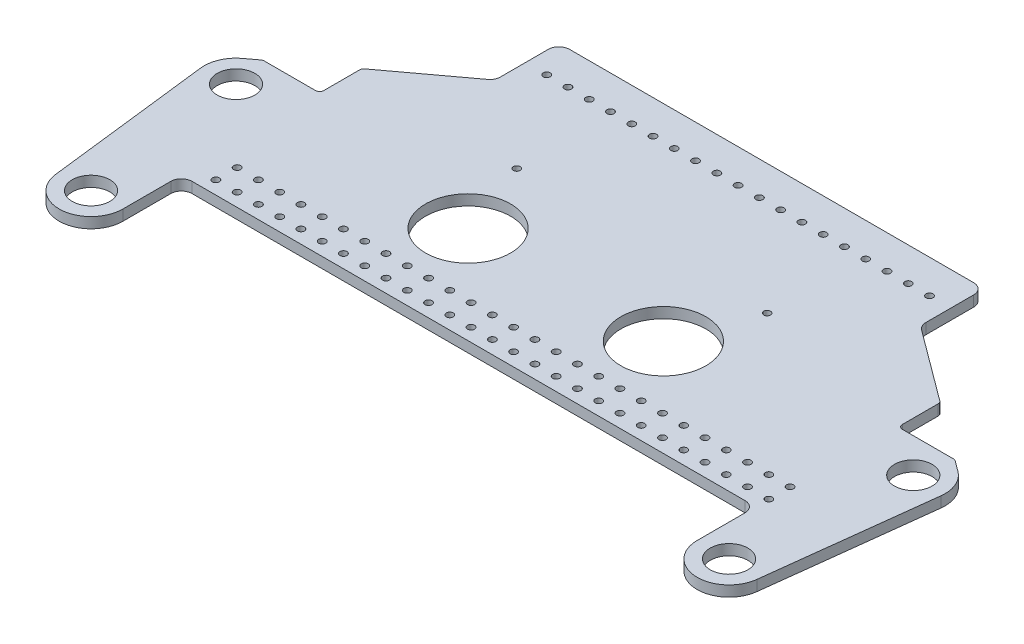
SolidWorks part; units mm, degrees
material "Air"
ref_plane "Front" through (0, 0, 0) normal (0, 0, 1) x (1, 0, 0)
ref_plane "Top" through (0, 0, 0) normal (0, 1, 0) x (1, 0, 0)
ref_plane "Right" through (0, 0, 0) normal (1, 0, 0) x (0, 0, -1)
sketch "Sketch1" plane through (0, 0, 0) normal (0, 1, 0) x (1, 0, 0)
  line L0 (0, 0) -> (0, 105.6961) construction
  line L1 (-202.2177, 98.3041) -> (-190.5, 0) construction
  line L2 (-127, 215.9) -> (127, 215.9)
  line L3 (-127, 215.9) -> (-127, 177.8)
  line L4 (-127, 177.8) -> (127, 177.8) construction
  line L5 (127, 215.9) -> (127, 177.8)
  line L6 (-190.839, 99.6604) -> (-179.1214, 1.3563) construction
  line L7 (-213.5963, 96.9478) -> (-201.8786, -1.3563) construction
  line L8 (-202.2177, 98.3041) -> (-58.3167, 92.964) construction
  line L9 (-201.7927, 109.7554) -> (-57.8917, 104.4153) construction
  line L10 (-202.6426, 86.8528) -> (-58.7416, 81.5127) construction
  line L11 (-190.5, 0) -> (-190.5, 152.4) construction
  line L12 (-190.5, 152.4) -> (74.7667, 138.4884) construction
  line L13 (-190.5, 0) -> (-127.3007, 138.6781) construction
  line L14 (-127.3007, 138.6781) -> (74.7667, 138.4884) construction
  line L15 (-209.55, 165.4952) -> (-209.55, -81.8808) construction
  line L16 (-171.45, 0) -> (-171.45, 34.925)
  line L17 (-205.8838, 91.9541) -> (-198.5515, 91.9541) construction
  line L18 (-198.5515, 91.9541) -> (-194.8853, 98.3041) construction
  line L19 (-194.8853, 98.3041) -> (-198.5515, 104.6541) construction
  line L20 (-198.5515, 104.6541) -> (-205.8838, 104.6541) construction
  line L21 (-205.8838, 104.6541) -> (-209.55, 98.3041) construction
  line L22 (-209.55, 98.3041) -> (-205.8838, 91.9541) construction
  line L23 (-171.45, 34.925) -> (171.45, 34.925)
  line L24 (171.45, 0) -> (171.45, 34.925)
  line L26 (-221.1337, 96.0493) -> (-209.4161, -2.2548)
  line L27 (-79.3225, 115.189) -> (-37.3109, 115.189) construction
  line L28 (-79.3225, 115.189) -> (-79.3225, 70.739) construction
  line L29 (-79.3225, 70.739) -> (-37.3109, 70.739) construction
  line L30 (-37.3109, 115.189) -> (-37.3109, 70.739) construction
  line L31 (-79.3225, 115.189) -> (-37.3109, 70.739) construction
  line L32 (-79.3225, 70.739) -> (-37.3109, 115.189) construction
  line L33 (-213.565, 113.6058) -> (-127, 177.8)
  line L34 (213.565, 113.6058) -> (127, 177.8)
  line L35 (221.1337, 96.0493) -> (209.4161, -2.2548)
  line L36 (-171.45, 34.925) -> (-171.45, 73.025) construction
  line L37 (-171.45, 73.025) -> (171.45, 73.025) construction
  line L38 (171.45, 73.025) -> (171.45, 34.925) construction
  line L39 (-177.8, 131.8554) -> (-177.8, -43.5528) construction
  line L40 (-440.324, 48.2727) -> (417.5697, 48.2727) construction
  circle A0 centre (-74.7667, 138.4884) radius 2.0193
  circle A1 centre (-190.5, 0) radius 11.2395
  circle A2 centre (74.7667, 138.4884) radius 2.0193
  circle A3 centre (190.5, 0) radius 11.2395
  circle A4 centre (-190.5, 0) radius 19.05 construction
  circle A5 centre (190.5, 0) radius 19.05 construction
  circle A6 centre (-202.2177, 98.3041) radius 11.2395
  arc A8 (-190.839, 99.6604) -> (-213.5963, 96.9478) centre (-202.2177, 98.3041) ccw construction
  arc A9 (-201.8786, -1.3563) -> (-179.1214, 1.3563) centre (-190.5, 0) ccw construction
  arc A10 (-201.7927, 109.7554) -> (-202.6426, 86.8528) centre (-202.2177, 98.3041) ccw construction
  arc A11 (-58.7416, 81.5127) -> (-57.8917, 104.4153) centre (-58.3167, 92.964) ccw construction
  circle A12 centre (-202.2177, 98.3041) radius 6.35 construction
  circle A13 centre (-202.2177, 98.3041) radius 7.3323 construction
  circle A14 centre (-202.2177, 98.3041) radius 19.05 construction
  arc A18 (-209.4161, -2.2548) -> (-171.45, 0) centre (-190.5, 0) ccw
  arc A19 (-221.1337, 96.0493) -> (-213.565, 113.6058) centre (-202.2177, 98.3041) cw
  arc A22 (221.1337, 96.0493) -> (213.565, 113.6058) centre (202.2177, 98.3041) ccw
  circle A23 centre (202.2177, 98.3041) radius 11.2395
  arc A24 (209.4161, -2.2548) -> (171.45, 0) centre (190.5, 0) cw
  circle A25 centre (-58.3167, 92.964) radius 25.4
  circle A26 centre (58.3167, 92.964) radius 25.4
  point P19 (-196.3588, 49.1521)
  point P24 (-130.2672, 95.6341)
  dimension "D4" = 22.479
  dimension "D5" = 38.1
  dimension "D6" = 4.0386
  dimension "D25" = 22.479
  dimension "D26" = 50.8
  dimension "D2" = 138.4884
  dimension "D7" = 254
  dimension "D8" = 38.1
  dimension "D9" = 22.9183
  dimension "D10" = 152.4
  dimension "D11" = 24.5
  dimension "D12" = 19.05
  dimension "D16" = 12.7
  dimension "D14" = 34.925
  dimension "D17" = 25.4
  dimension "D21" = 44.45
  dimension "D22" = 42.0116
  dimension "D24" = 38.1
  dimension "D23" = 2.286
  dimension "D27" = 177.8
  dimension "D28" = 167.6273
  dimension "D3" = 265.2667
  dimension "D29" = 342.9
extrude "Boss-Extrude1" add sketch "Sketch1" along normal mid plane 6.35
fillet "Fillet1" radius 6.35 6 edges at (-127, 0, -177.8) (-127, 0, -215.9) (127, 0, -215.9) (127, 0, -177.8) (171.45, 0, -34.925) (-171.45, 0, -34.925)
sketch "Sketch2" plane through (0, 3.175, 0) normal (0, 1, 0) x (1, 0, 0)
  line L0 (-127, 195.9049) -> (127, 195.9049) construction
  line L2 (127, 209.55) -> (127, 180.9965) construction
  line L3 (0, 195.9049) -> (0, 215.9) construction
  line L4 (-120.65, 215.9) -> (120.65, 215.9) construction
  circle A0 centre (0, 208.6049) radius 2.0828 construction
  circle A1 centre (12.7, 208.6049) radius 2.0828 construction
  circle A2 centre (25.4, 208.6049) radius 2.0828 construction
  circle A3 centre (38.1, 208.6049) radius 2.0828 construction
  circle A4 centre (50.8, 208.6049) radius 2.0828 construction
  circle A5 centre (63.5, 208.6049) radius 2.0828 construction
  circle A6 centre (76.2, 208.6049) radius 2.0828 construction
  circle A7 centre (88.9, 208.6049) radius 2.0828 construction
  circle A8 centre (101.6, 208.6049) radius 2.0828 construction
  circle A9 centre (114.3, 208.6049) radius 2.0828 construction
  circle A10 centre (12.7, 195.9049) radius 2.0828
  circle A11 centre (25.4, 195.9049) radius 2.0828
  circle A12 centre (38.1, 195.9049) radius 2.0828
  circle A13 centre (50.8, 195.9049) radius 2.0828
  circle A14 centre (63.5, 195.9049) radius 2.0828
  circle A15 centre (76.2, 195.9049) radius 2.0828
  circle A16 centre (88.9, 195.9049) radius 2.0828
  circle A17 centre (101.6, 195.9049) radius 2.0828
  circle A18 centre (114.3, 195.9049) radius 2.0828
  circle A19 centre (12.7, 183.2049) radius 2.0828 construction
  circle A20 centre (25.4, 183.2049) radius 2.0828 construction
  circle A21 centre (38.1, 183.2049) radius 2.0828 construction
  circle A22 centre (50.8, 183.2049) radius 2.0828 construction
  circle A23 centre (63.5, 183.2049) radius 2.0828 construction
  circle A24 centre (76.2, 183.2049) radius 2.0828 construction
  circle A25 centre (88.9, 183.2049) radius 2.0828 construction
  circle A26 centre (101.6, 183.2049) radius 2.0828 construction
  circle A27 centre (114.3, 183.2049) radius 2.0828 construction
  circle A29 centre (0, 183.2049) radius 2.0828 construction
  circle A33 centre (0, 183.2049) radius 2.0828 construction
  circle A34 centre (0, 195.9049) radius 2.0828
  circle A35 centre (-114.3, 183.2049) radius 2.0828 construction
  circle A36 centre (-101.6, 183.2049) radius 2.0828 construction
  circle A37 centre (-88.9, 183.2049) radius 2.0828 construction
  circle A38 centre (-76.2, 183.2049) radius 2.0828 construction
  circle A39 centre (-63.5, 183.2049) radius 2.0828 construction
  circle A40 centre (-50.8, 183.2049) radius 2.0828 construction
  circle A41 centre (-38.1, 183.2049) radius 2.0828 construction
  circle A42 centre (-25.4, 183.2049) radius 2.0828 construction
  circle A43 centre (-12.7, 183.2049) radius 2.0828 construction
  circle A44 centre (-114.3, 195.9049) radius 2.0828
  circle A45 centre (-101.6, 195.9049) radius 2.0828
  circle A46 centre (-88.9, 195.9049) radius 2.0828
  circle A47 centre (-76.2, 195.9049) radius 2.0828
  circle A48 centre (-63.5, 195.9049) radius 2.0828
  circle A49 centre (-50.8, 195.9049) radius 2.0828
  circle A50 centre (-38.1, 195.9049) radius 2.0828
  circle A51 centre (-25.4, 195.9049) radius 2.0828
  circle A52 centre (-12.7, 195.9049) radius 2.0828
  circle A53 centre (-114.3, 208.6049) radius 2.0828 construction
  circle A54 centre (-101.6, 208.6049) radius 2.0828 construction
  circle A55 centre (-88.9, 208.6049) radius 2.0828 construction
  circle A56 centre (-76.2, 208.6049) radius 2.0828 construction
  circle A57 centre (-63.5, 208.6049) radius 2.0828 construction
  circle A58 centre (-50.8, 208.6049) radius 2.0828 construction
  circle A59 centre (-38.1, 208.6049) radius 2.0828 construction
  circle A60 centre (-25.4, 208.6049) radius 2.0828 construction
  circle A61 centre (-12.7, 208.6049) radius 2.0828 construction
  circle A62 centre (0, 208.6049) radius 2.0828 construction
  circle A63 centre (0, 195.9049) radius 2.0828 [skipped]
  dimension "D1" = 4.1656
  dimension "D4" = 12.7
  dimension "D5" = 19.9951
  dimension "D6" = 12.7
  dimension "D7" = 12.7
  dimension "D2" = 10
  dimension "D3" = 3
extrude "Cut-Extrude1" cut sketch "Sketch2" against normal through all
sketch "Sketch3" plane through (0, 3.175, 0) normal (0, 1, 0) x (1, 0, 0)
  line L0 (-165.1, 34.925) -> (165.1, 34.925) construction
  line L1 (0, -18.3754) -> (0, 153.3377) construction
  circle A0 centre (0, 42.799) radius 2.0828 construction
  circle A1 centre (12.7, 42.799) radius 2.0828 construction
  circle A2 centre (25.4, 42.799) radius 2.0828 construction
  circle A3 centre (38.1, 42.799) radius 2.0828 construction
  circle A4 centre (50.8, 42.799) radius 2.0828 construction
  circle A5 centre (63.5, 42.799) radius 2.0828 construction
  circle A6 centre (76.2, 42.799) radius 2.0828 construction
  circle A7 centre (88.9, 42.799) radius 2.0828 construction
  circle A8 centre (101.6, 42.799) radius 2.0828 construction
  circle A9 centre (114.3, 42.799) radius 2.0828 construction
  circle A10 centre (127, 42.799) radius 2.0828 construction
  circle A11 centre (139.7, 42.799) radius 2.0828 construction
  circle A12 centre (152.4, 42.799) radius 2.0828 construction
  circle A13 centre (165.1, 42.799) radius 2.0828 construction
  circle A14 centre (12.7, 55.499) radius 2.0828 construction
  circle A15 centre (25.4, 55.499) radius 2.0828 construction
  circle A16 centre (38.1, 55.499) radius 2.0828 construction
  circle A17 centre (50.8, 55.499) radius 2.0828 construction
  circle A18 centre (63.5, 55.499) radius 2.0828 construction
  circle A19 centre (76.2, 55.499) radius 2.0828 construction
  circle A20 centre (88.9, 55.499) radius 2.0828 construction
  circle A21 centre (101.6, 55.499) radius 2.0828 construction
  circle A22 centre (114.3, 55.499) radius 2.0828 construction
  circle A23 centre (127, 55.499) radius 2.0828 construction
  circle A24 centre (139.7, 55.499) radius 2.0828 construction
  circle A25 centre (152.4, 55.499) radius 2.0828 construction
  circle A26 centre (165.1, 55.499) radius 2.0828 construction
  circle A27 centre (12.7, 68.199) radius 2.0828 construction
  circle A28 centre (25.4, 68.199) radius 2.0828 construction
  circle A29 centre (38.1, 68.199) radius 2.0828 construction
  circle A30 centre (50.8, 68.199) radius 2.0828 construction
  circle A31 centre (63.5, 68.199) radius 2.0828 construction
  circle A32 centre (76.2, 68.199) radius 2.0828 construction
  circle A33 centre (88.9, 68.199) radius 2.0828 construction
  circle A34 centre (101.6, 68.199) radius 2.0828 construction
  circle A35 centre (114.3, 68.199) radius 2.0828 construction
  circle A36 centre (127, 68.199) radius 2.0828 construction
  circle A37 centre (139.7, 68.199) radius 2.0828 construction
  circle A38 centre (152.4, 68.199) radius 2.0828 construction
  circle A39 centre (165.1, 68.199) radius 2.0828 construction
  circle A40 centre (0, 55.499) radius 2.0828 construction
  circle A41 centre (0, 68.199) radius 2.0828 construction
  circle A42 centre (-165.1, 68.199) radius 2.0828 construction
  circle A43 centre (-152.4, 68.199) radius 2.0828 construction
  circle A44 centre (-139.7, 68.199) radius 2.0828 construction
  circle A45 centre (-127, 68.199) radius 2.0828 construction
  circle A46 centre (-114.3, 68.199) radius 2.0828 construction
  circle A47 centre (-101.6, 68.199) radius 2.0828 construction
  circle A48 centre (-88.9, 68.199) radius 2.0828 construction
  circle A49 centre (-76.2, 68.199) radius 2.0828 construction
  circle A50 centre (-63.5, 68.199) radius 2.0828 construction
  circle A51 centre (-50.8, 68.199) radius 2.0828 construction
  circle A52 centre (-38.1, 68.199) radius 2.0828 construction
  circle A53 centre (-25.4, 68.199) radius 2.0828 construction
  circle A54 centre (-12.7, 68.199) radius 2.0828 construction
  circle A55 centre (-165.1, 55.499) radius 2.0828 construction
  circle A56 centre (-152.4, 55.499) radius 2.0828 construction
  circle A57 centre (-139.7, 55.499) radius 2.0828 construction
  circle A58 centre (-127, 55.499) radius 2.0828 construction
  circle A59 centre (-114.3, 55.499) radius 2.0828 construction
  circle A60 centre (-101.6, 55.499) radius 2.0828 construction
  circle A61 centre (-88.9, 55.499) radius 2.0828 construction
  circle A62 centre (-76.2, 55.499) radius 2.0828 construction
  circle A63 centre (-63.5, 55.499) radius 2.0828 construction
  circle A64 centre (-50.8, 55.499) radius 2.0828 construction
  circle A65 centre (-38.1, 55.499) radius 2.0828 construction
  circle A66 centre (-25.4, 55.499) radius 2.0828 construction
  circle A67 centre (-12.7, 55.499) radius 2.0828 construction
  circle A68 centre (-165.1, 42.799) radius 2.0828 construction
  circle A69 centre (-152.4, 42.799) radius 2.0828 construction
  circle A70 centre (-139.7, 42.799) radius 2.0828 construction
  circle A71 centre (-127, 42.799) radius 2.0828 construction
  circle A72 centre (-114.3, 42.799) radius 2.0828 construction
  circle A73 centre (-101.6, 42.799) radius 2.0828 construction
  circle A74 centre (-88.9, 42.799) radius 2.0828 construction
  circle A75 centre (-76.2, 42.799) radius 2.0828 construction
  circle A76 centre (-63.5, 42.799) radius 2.0828 construction
  circle A77 centre (-50.8, 42.799) radius 2.0828 construction
  circle A78 centre (-38.1, 42.799) radius 2.0828 construction
  circle A79 centre (-25.4, 42.799) radius 2.0828 construction
  circle A80 centre (-12.7, 42.799) radius 2.0828 construction
  circle A81 centre (6.35, 42.799) radius 2.0828
  circle A82 centre (19.05, 42.799) radius 2.0828
  circle A83 centre (31.75, 42.799) radius 2.0828
  circle A84 centre (44.45, 42.799) radius 2.0828
  circle A85 centre (57.15, 42.799) radius 2.0828
  circle A86 centre (69.85, 42.799) radius 2.0828
  circle A87 centre (82.55, 42.799) radius 2.0828
  circle A88 centre (95.25, 42.799) radius 2.0828
  circle A89 centre (107.95, 42.799) radius 2.0828
  circle A90 centre (120.65, 42.799) radius 2.0828
  circle A91 centre (133.35, 42.799) radius 2.0828
  circle A92 centre (146.05, 42.799) radius 2.0828
  circle A93 centre (158.75, 42.799) radius 2.0828
  circle A94 centre (171.45, 42.799) radius 2.0828
  circle A95 centre (19.05, 55.499) radius 2.0828
  circle A96 centre (31.75, 55.499) radius 2.0828
  circle A97 centre (44.45, 55.499) radius 2.0828
  circle A98 centre (57.15, 55.499) radius 2.0828
  circle A99 centre (69.85, 55.499) radius 2.0828
  circle A100 centre (82.55, 55.499) radius 2.0828
  circle A101 centre (95.25, 55.499) radius 2.0828
  circle A102 centre (107.95, 55.499) radius 2.0828
  circle A103 centre (120.65, 55.499) radius 2.0828
  circle A104 centre (133.35, 55.499) radius 2.0828
  circle A105 centre (146.05, 55.499) radius 2.0828
  circle A106 centre (158.75, 55.499) radius 2.0828
  circle A107 centre (171.45, 55.499) radius 2.0828
  circle A108 centre (6.35, 55.499) radius 2.0828
  circle A109 centre (-158.75, 55.499) radius 2.0828
  circle A110 centre (-146.05, 55.499) radius 2.0828
  circle A111 centre (-133.35, 55.499) radius 2.0828
  circle A112 centre (-120.65, 55.499) radius 2.0828
  circle A113 centre (-107.95, 55.499) radius 2.0828
  circle A114 centre (-95.25, 55.499) radius 2.0828
  circle A115 centre (-82.55, 55.499) radius 2.0828
  circle A116 centre (-69.85, 55.499) radius 2.0828
  circle A117 centre (-57.15, 55.499) radius 2.0828
  circle A118 centre (-44.45, 55.499) radius 2.0828
  circle A119 centre (-31.75, 55.499) radius 2.0828
  circle A120 centre (-19.05, 55.499) radius 2.0828
  circle A121 centre (-6.35, 55.499) radius 2.0828
  circle A122 centre (-158.75, 42.799) radius 2.0828
  circle A123 centre (-146.05, 42.799) radius 2.0828
  circle A124 centre (-133.35, 42.799) radius 2.0828
  circle A125 centre (-120.65, 42.799) radius 2.0828
  circle A126 centre (-107.95, 42.799) radius 2.0828
  circle A127 centre (-95.25, 42.799) radius 2.0828
  circle A128 centre (-82.55, 42.799) radius 2.0828
  circle A129 centre (-69.85, 42.799) radius 2.0828
  circle A130 centre (-57.15, 42.799) radius 2.0828
  circle A131 centre (-44.45, 42.799) radius 2.0828
  circle A132 centre (-31.75, 42.799) radius 2.0828
  circle A133 centre (-19.05, 42.799) radius 2.0828
  circle A134 centre (-6.35, 42.799) radius 2.0828
  dimension "D1" = 4.1656
  dimension "D2" = 7.874
  dimension "D5" = 12.7
  dimension "D6" = 12.7
  dimension "D7" = 2
  dimension "D8" = 6.35
  dimension "D3" = 14
  dimension "D4" = 3
extrude "Cut-Extrude2" cut sketch "Sketch3" against normal through all
sketch "Sketch4" plane through (0, 3.175, 0) normal (0, 1, 0) x (1, 0, 0)
  line L0 (-172.72, 143.8953) -> (-172.72, 118.745)
  line L1 (-213.565, 113.6058) -> (-129.5676, 175.896) construction
  line L2 (-172.72, 118.745) -> (-206.6348, 118.745)
  line L3 (-127, 209.55) -> (-127, 180.9965) construction
  line L4 (-165.1, 34.925) -> (165.1, 34.925) construction
  line L5 (-206.6348, 118.745) -> (-172.72, 143.8953)
  line L6 (0, -70.7269) -> (0, 276.761) construction
  line L7 (172.72, 118.745) -> (206.6348, 118.745)
  line L8 (206.6348, 118.745) -> (172.72, 143.8953)
  line L9 (172.72, 143.8953) -> (172.72, 118.745)
  dimension "D1" = 45.72
  dimension "D2" = 83.82
extrude "Cut-Extrude3" cut sketch "Sketch4" against normal up to next
fillet "Fillet2" radius 2.54 6 edges at (-206.6348, 0, -118.745) (-172.72, 0, -143.8953) (-172.72, 0, -118.745) (206.6348, 0, -118.745) (172.72, 0, -118.745) (172.72, 0, -143.8953)
equation "\"D9@Sketch1\"=3mm*24/pi"
equation "\"D13@Sketch1\"=3mm*90"
equation "\"D15@Sketch1\"=3mm*120"
